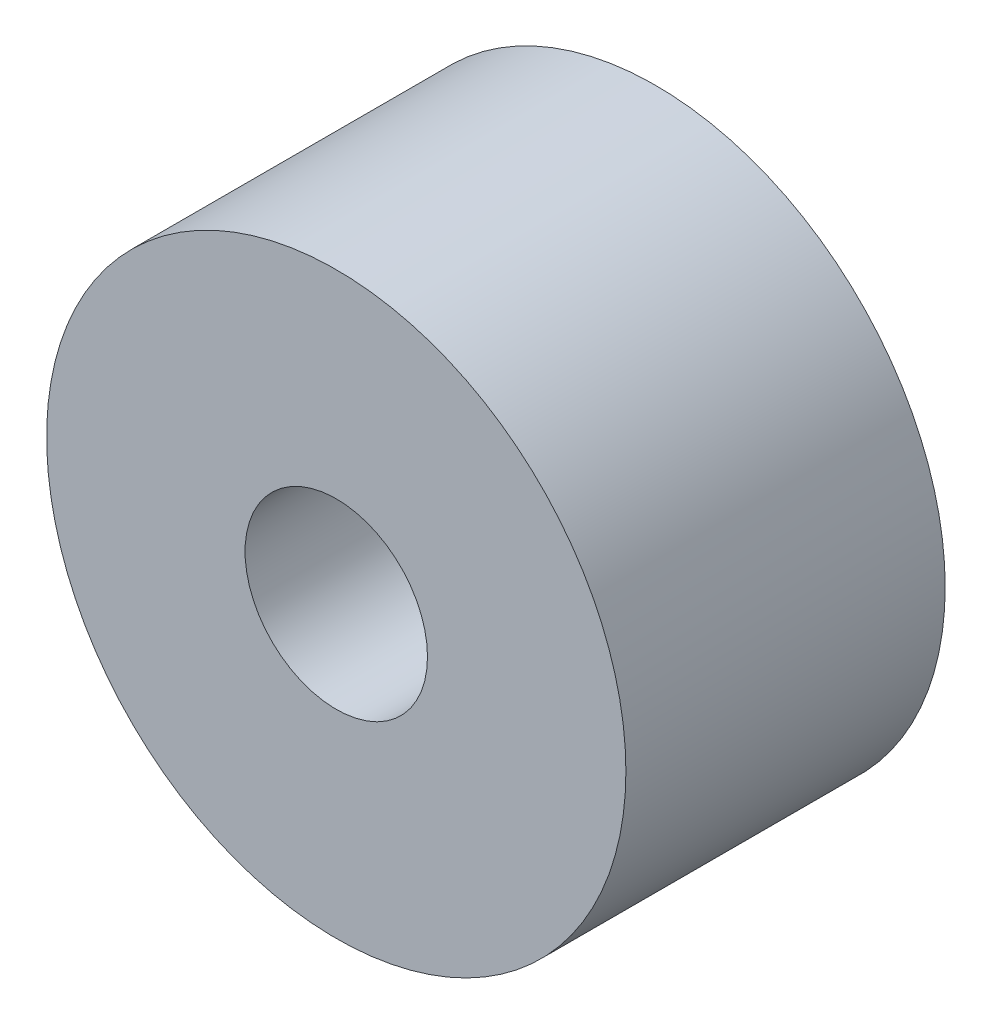
SolidWorks part; units mm, degrees
ref_plane "Front Plane" through (0, 0, 0) normal (0, 0, 1) x (1, 0, 0)
ref_plane "Top Plane" through (0, 0, 0) normal (0, 1, 0) x (1, 0, 0)
ref_plane "Right Plane" through (0, 0, 0) normal (1, 0, 0) x (0, 0, -1)
sketch "Sketch1" plane through (0, 0, 0) normal (0, 0, 1) x (1, 0, 0)
  circle A0 centre (0, 0) radius 12.7
  dimension "D1" = 25.4
extrude "Boss-Extrude1" add sketch "Sketch1" along normal blind 2
sketch "Sketch2" plane through (0, 0, 2) normal (0, 0, 1) x (1, 0, 0)
  circle A1 centre (0, 0) radius 4
  circle A2 centre (0, 0) radius 12.7 construction
  circle A3 centre (0, 0) radius 12.7
  dimension "D1" = 8
extrude "Boss-Extrude2" add sketch "Sketch2" along normal blind 12
